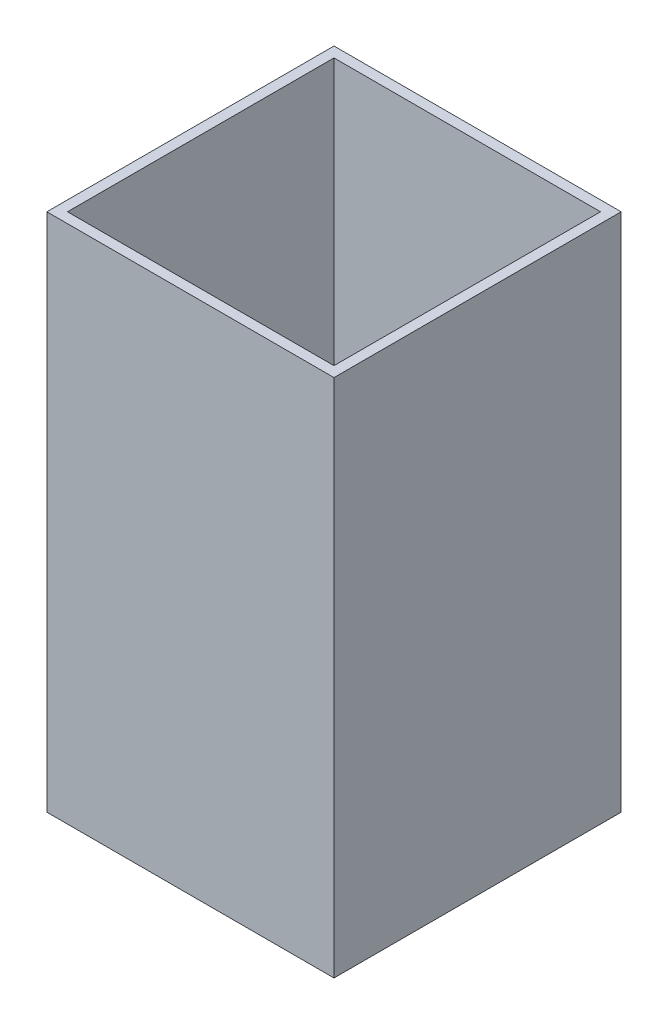
SolidWorks part; units mm, degrees
ref_plane "Front Plane" through (0, 0, 0) normal (0, 0, 1) x (1, 0, 0)
ref_plane "Top Plane" through (0, 0, 0) normal (0, 1, 0) x (1, 0, 0)
ref_plane "Right Plane" through (0, 0, 0) normal (1, 0, 0) x (0, 0, -1)
sketch "Sketch1" plane through (0, 0, 0) normal (0, 1, 0) x (1, 0, 0)
  line L1 (0, 0) -> (88.35, 0)
  line L2 (0, 0) -> (0, 88.35)
  line L3 (0, 88.35) -> (88.35, 88.35)
  line L4 (88.35, 0) -> (88.35, 88.35)
  line L5 (3.175, 3.175) -> (85.175, 3.175)
  line L6 (3.175, 3.175) -> (3.175, 85.175)
  line L7 (3.175, 85.175) -> (85.175, 85.175)
  line L8 (85.175, 3.175) -> (85.175, 85.175)
  line L9 (3.175, 85.175) -> (0, 85.175) construction
  line L10 (3.175, 85.175) -> (3.175, 88.35) construction
  line L11 (85.175, 3.175) -> (85.175, 0) construction
  line L12 (85.175, 3.175) -> (88.35, 3.175) construction
  dimension "D1" = 82
  dimension "D2" = 3.175
extrude "Boss-Extrude1" add sketch "Sketch1" along normal blind 160
sketch "Sketch2" plane through (0, 0, 0) normal (0, -1, 0) x (1, 0, 0)
  line L1 (0, 0) -> (88.35, 0)
  line L2 (0, 0) -> (0, -88.35)
  line L3 (0, -88.35) -> (88.35, -88.35)
  line L4 (88.35, 0) -> (88.35, -88.35)
extrude "Boss-Extrude2" add sketch "Sketch2" against normal blind 3.175
